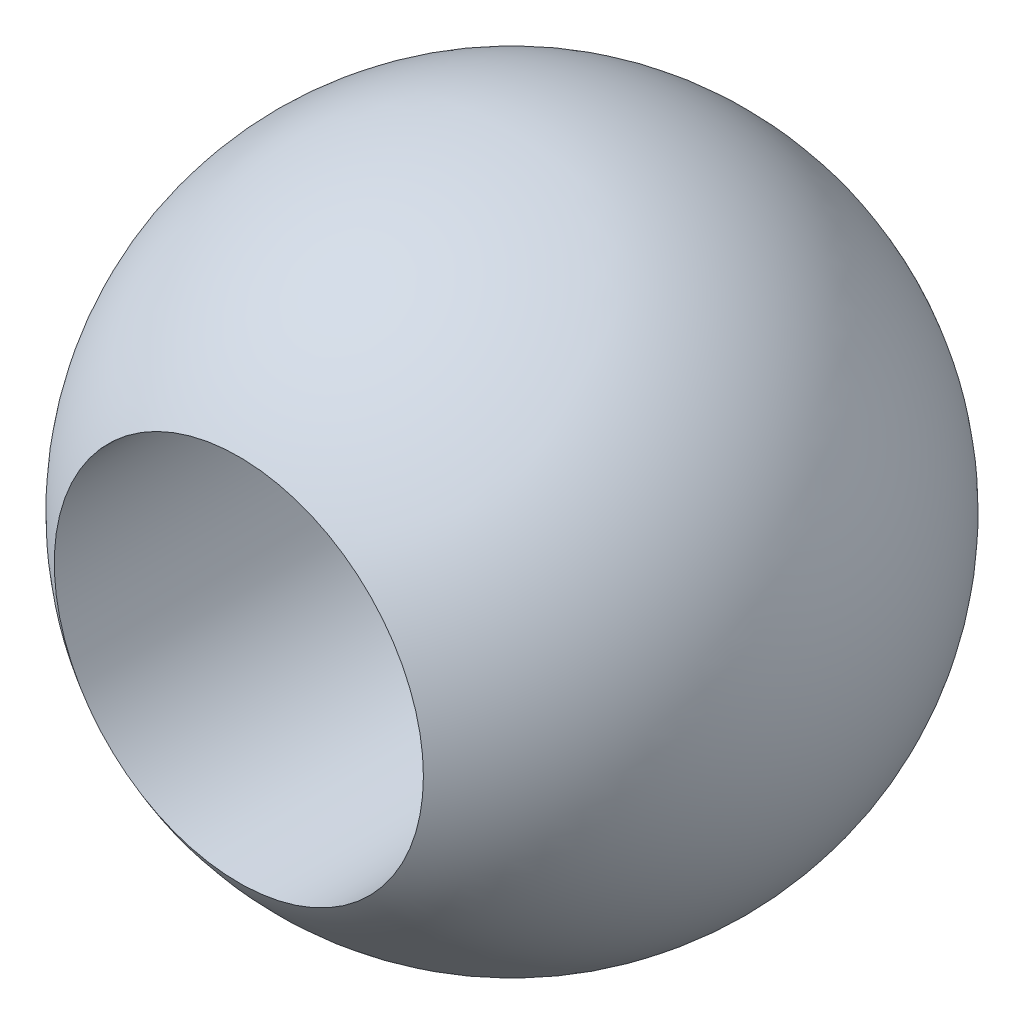
SolidWorks part; units mm, degrees
ref_plane "Front Plane" through (0, 0, 0) normal (0, 0, 1) x (1, 0, 0)
ref_plane "Top Plane" through (0, 0, 0) normal (0, 1, 0) x (1, 0, 0)
ref_plane "Right Plane" through (0, 0, 0) normal (1, 0, 0) x (0, 0, -1)
sketch "Sketch2" plane through (0, 0, 0) normal (0, 0, 1) x (1, 0, 0)
  line L0 (0, -1000) -> (0, 49000) construction
  line L1 (0, 14.2875) -> (0, -14.2875)
  arc A0 (0, -14.2875) -> (0, 14.2875) centre (0, 0) ccw
  dimension "D1" = 28.575
revolve "Revolve1" add sketch "Sketch2" angle 360 about L0
sketch "Sketch3" plane through (0, 0, 0) normal (0, 0, 1) x (1, 0, 0)
  circle A0 centre (0, 0) radius 8
  dimension "D1" = 16
extrude "Cut-Extrude1" cut sketch "Sketch3" against normal through all both and the other way through all
